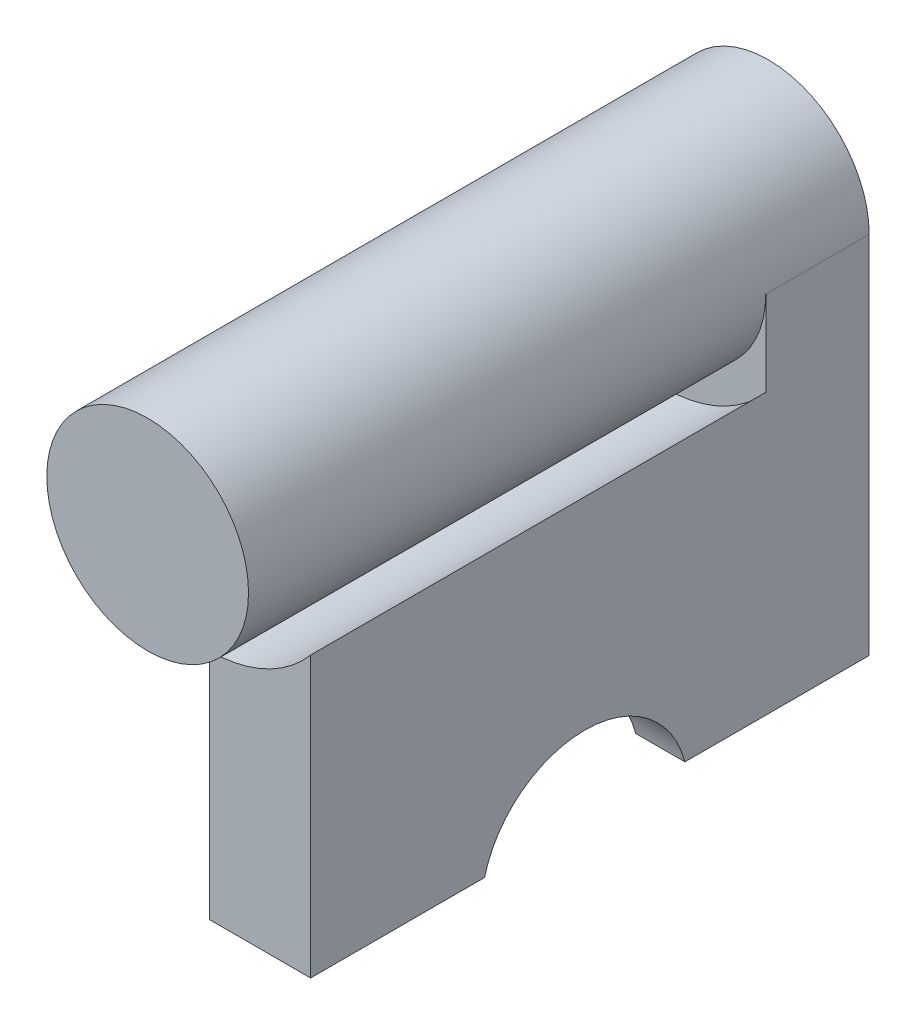
SolidWorks part; units mm, degrees
ref_plane "정면" through (0, 0, 0) normal (0, 0, 1) x (1, 0, 0)
ref_plane "윗면" through (0, 0, 0) normal (0, 1, 0) x (1, 0, 0)
ref_plane "우측면" through (0, 0, 0) normal (1, 0, 0) x (0, 0, -1)
sketch "스케치1" plane through (0, 0, 0) normal (0, 0, 1) x (1, 0, 0)
  circle A0 centre (0, 0) radius 1.95
  dimension "D1" = 3.9
extrude "보스-돌출1" add sketch "스케치1" along normal blind 12
sketch "스케치4" plane through (0, 0, 0) normal (1, 0, 0) x (0, 0, -1)
  line L5 (-2, 1.95) -> (0, 1.95)
  line L6 (-2, 1.95) -> (-2, -7.05)
  line L7 (-2, -7.05) -> (0, -7.05)
  line L8 (0, 1.95) -> (0, -7.05)
  line L9 (-2, 1.95) -> (0, -7.05) construction
  line L10 (-2, -7.05) -> (0, 1.95) construction
  point P0 (-1, -2.55)
  dimension "D1" = 2
  dimension "D2" = 9
extrude "보스-돌출2" add sketch "스케치4" along normal blind 1.95
sketch "스케치8" plane through (0, 0, 2) normal (0, 0, 1) x (1, 0, 0)
  line L0 (0, -1.95) -> (0, -7.05)
  line L1 (0, -7.05) -> (1.95, -7.05)
  line L2 (1.95, -7.05) -> (1.95, -1.6432)
  line L3 (0, -2.55) -> (0, -7.05)
  line L4 (1.95, -7.05) -> (1.95, -1.6432)
  line L5 (1.95, 0) -> (1.95, -7.05) construction
  line L6 (0, -1.95) -> (0, -7.05) construction
  circle A0 centre (0, 0) radius 1.95 construction
  circle A2 centre (0, 0) radius 1.95
  circle A3 centre (0, 0) radius 1.95
  circle A5 centre (0, 0) radius 2.55
  dimension "D2" = 5.1
  dimension "D1" = 0
extrude "보스-돌출4" add sketch "스케치8" along normal blind 8.8
sketch "스케치9" plane through (0, 0, 0) normal (-1, 0, 0) x (0, 0, 1)
  line L1 (12, -1.95) -> (12, 1.95) construction
  line L6 (10.8, -7.05) -> (0, -7.05) construction
  circle A0 centre (5.5, -7.55) radius 2
  dimension "D1" = 4
  dimension "D2" = 6.5
  dimension "D3" = 0.5
extrude "컷-돌출2" cut sketch "스케치9" against normal blind 17
sketch "스케치12" plane through (0, 0, 2) normal (0, 0, 1) x (1, 0, 0)
  line L0 (0, 1.95) -> (1.95, 1.95)
  line L1 (1.95, 1.95) -> (1.95, 0)
  circle A1 centre (0, 0) radius 1.95
  line M7 (1.95, 1.95) -> (0, 1.95)
  arc M8 (0, 1.95) -> (1.95, 0) centre (0, 0) cw
  line M9 (1.95, 0) -> (1.95, 1.95)
sketch "스케치13" plane through (0, 0, 0) normal (-1, 0, 0) x (0, 0, 1)
  line L0 (10.8, -7.05) -> (7.4365, -7.05) construction
  line L2 (0, -7.05) -> (0, -1.95) construction
  circle A0 centre (5.505, -7.55) radius 2.75
  dimension "D1" = 0.5
  dimension "D2" = 5.5
  dimension "D3" = 5.505
extrude "컷-돌출6" cut sketch "스케치13" against normal blind 1
extrude "컷-돌출7" cut sketch "스케치12" against normal through all contours M9 M7 M8
equation "\"15.9.00mm\"= 15.9"
equation "\"D1@컷-돌출3\"=1.50mm"
